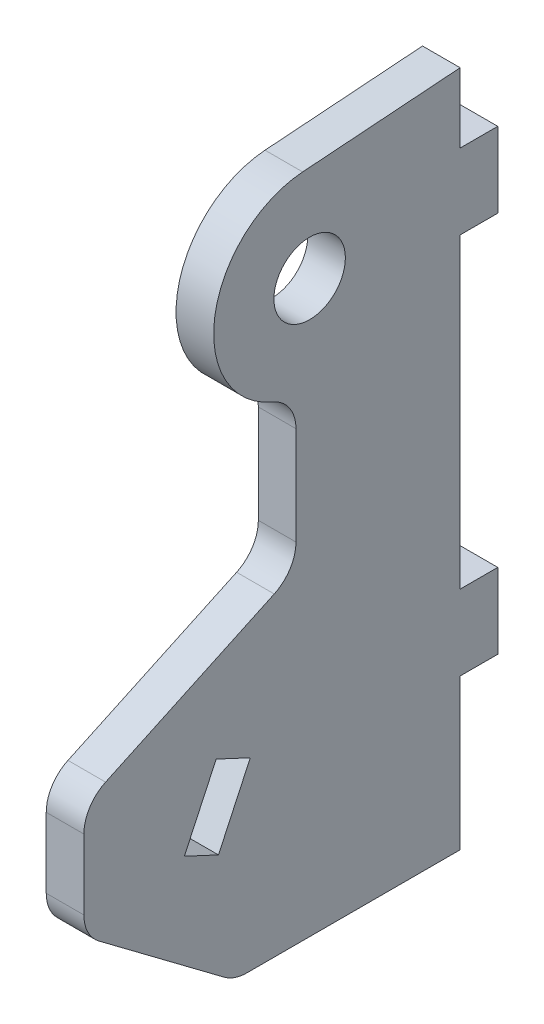
SolidWorks part; units mm, degrees
material "AISI 1020 Steel, Cold Rolled"
ref_plane "Front Plane" through (0, 0, 0) normal (1, 0, 0) x (0, 1, 0)
ref_plane "Top Plane" through (0, 0, 0) normal (0, 0, 1) x (0, 1, 0)
ref_plane "Right Plane" through (0, 0, 0) normal (0, 1, 0) x (-1, 0, 0)
sketch "Sketch1" plane through (0, 0, 0) normal (1, 0, 0) x (0, 1, 0)
  line L0 (-15.7577, 0) -> (-5, 0)
  line L1 (0, 0) -> (0, 20) construction
  line L2 (-15.7577, 0) -> (-12.6201, 21.8151) construction
  line L3 (14.2423, 0) -> (12.7162, 20.9273)
  line L4 (0, 0) -> (0, -5) construction
  line L5 (5, -5) -> (-5, -5)
  line L6 (-5, -5) -> (-5, 0)
  line L7 (5, -5) -> (5, 0)
  line L8 (5, 0) -> (14.2423, 0)
  line L9 (0, 0) -> (5, 0) construction
  line L10 (-5, 0) -> (0, 0) construction
  line L11 (0, 20) -> (0, 4.6155) construction
  line L12 (-15.7577, 0) -> (-75.7577, 0) construction
  line L13 (-75.7577, 0) -> (-75.7577, 50) construction
  line L14 (-75.7577, 50) -> (-45.7577, 50) construction
  line L15 (-45.7577, 50) -> (-32.6201, 21.8151)
  line L16 (-32.6201, 21.8151) -> (-12.6201, 21.8151) construction
  line L17 (-75.7577, 30) -> (-60.7577, 50)
  line L18 (-75.7577, 30) -> (-75.7577, 0)
  line L19 (-75.7577, 0) -> (-15.7577, 0)
  line L20 (-60.7577, 50) -> (-45.7577, 50)
  line L21 (-32.6201, 21.8151) -> (-12.6201, 21.8151)
  circle A0 centre (0, 20) radius 4.75
  arc A1 (12.7162, 20.9273) -> (-12.6201, 21.8151) centre (0, 20) ccw
  arc A2 (0, 7.25) -> (12.7162, 20.9273) centre (0, 20) ccw construction
  circle A3 centre (0, 20) radius 12.75 construction
  point P4 (0, 0)
  point P11 (12, 20)
  point P17 (0, -5)
  dimension "D3" = 9.5
  dimension "D4" = 8
  dimension "D1" = 30
  dimension "D2" = 20
  dimension "D5" = 5
  dimension "D6" = 10
  dimension "D7" = 15.3845
  dimension "D8" = 60
  dimension "D9" = 50
  dimension "D10" = 30
  dimension "D13" = 20
  dimension "D14" = 20
  dimension "D15" = 15
extrude "Boss-Extrude1" add sketch "Sketch1" along normal mid plane 5
fillet "Fillet1" radius 5 5 edges at (0, -12.6201, 21.8151) (0, -32.6201, 21.8151) (0, -75.7577, 30) (0, -60.7577, 50) (0, -45.7577, 50)
sketch "Sketch2" plane through (2.5, 0, 0) normal (1, 0, 0) x (0, 1, 0)
  line L0 (-75.7577, 0) -> (-55.7577, 0)
  line L1 (-75.7577, 0) -> (-5, 0) construction
  line L2 (-55.7577, 0) -> (-55.7577, 30)
  line L3 (-51.2262, 27.8869) -> (-60.2893, 32.1131)
  line L4 (-36.8757, 30) -> (-74.6397, 30) construction
  line L5 (-49.1131, 32.4184) -> (-58.1762, 36.6446)
  line L6 (-51.2262, 27.8869) -> (-49.1131, 32.4184)
  line L7 (-60.2893, 32.1131) -> (-58.1762, 36.6446)
  point P9 (-55.7577, 30)
  point P12 (-55.7577, 30)
  dimension "D1" = 20
  dimension "D2" = 30
  dimension "D3" = 10
  dimension "D4" = 25
  dimension "D5" = 5
extrude "Cut-Extrude1" cut sketch "Sketch2" against normal up to next contours L5 L7 L3 L6
sketch "Sketch3" plane through (0, 0, 0) normal (0, 0, -1) x (1, 0, 0)
  line L0 (2.5, 75.7577) -> (2.5, 55.7577)
  line L1 (2.5, 75.7577) -> (2.5, 5) construction
  line L2 (-2.5, 75.7577) -> (-2.5, 5) construction
  line L3 (2.5, 55.7577) -> (-2.5, 55.7577)
  line L4 (2.5, 55.7577) -> (2.5, 45.7577)
  line L5 (2.5, 45.7577) -> (-2.5, 45.7577)
  line L6 (-2.5, 55.7577) -> (-2.5, 45.7577)
  line M4 (-2.5, 75.7577) -> (-2.5, 5)
  line M6 (2.5, 5) -> (2.5, 75.7577)
  dimension "D1" = 20
  dimension "D2" = 10
extrude "Boss-Extrude2" add sketch "Sketch3" along normal blind 5 contours L5 L3 M6 M4
